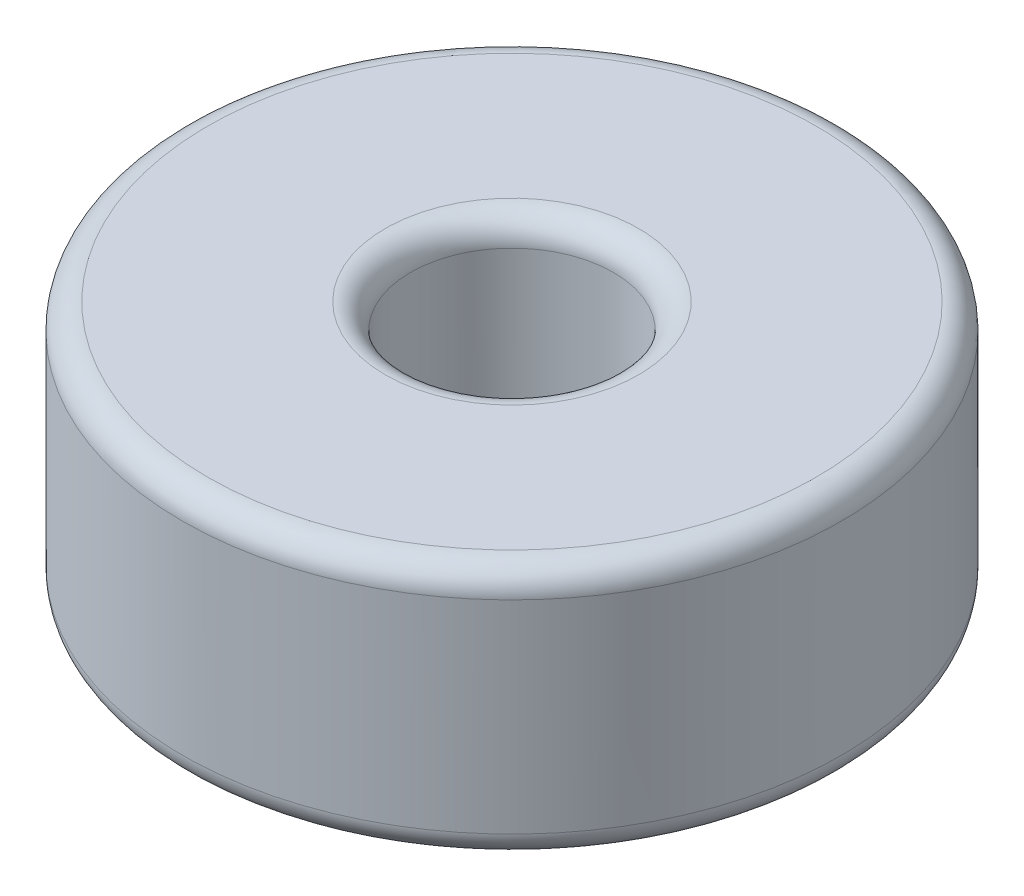
SolidWorks part; units mm, degrees
ref_plane "Plan de face" through (0, 0, 0) normal (0, 0, 1) x (1, 0, 0)
ref_plane "Plan de dessus" through (0, 0, 0) normal (0, 1, 0) x (1, 0, 0)
ref_plane "Plan de droite" through (0, 0, 0) normal (1, 0, 0) x (0, 0, -1)
sketch "Esquisse1" plane through (0, 0, 0) normal (0, 0, 1) x (1, 0, 0)
  line L0 (0, 0) -> (0, 20.4123) construction
  line L1 (2, 0) -> (6.5, 0)
  line L2 (2, 0) -> (2, 5)
  line L3 (2, 5) -> (6.5, 5)
  line L4 (6.5, 0) -> (6.5, 5)
  dimension "D1" = 4
  dimension "D2" = 13
  dimension "D3" = 5
revolve "Révolution1" add sketch "Esquisse1" angle 360 about L0
fillet "Congé1" radius 0.5 4 edges at (0, 0, -2) (0, 0, -6.5) (0, 5, -6.5) (0, 5, -2)
